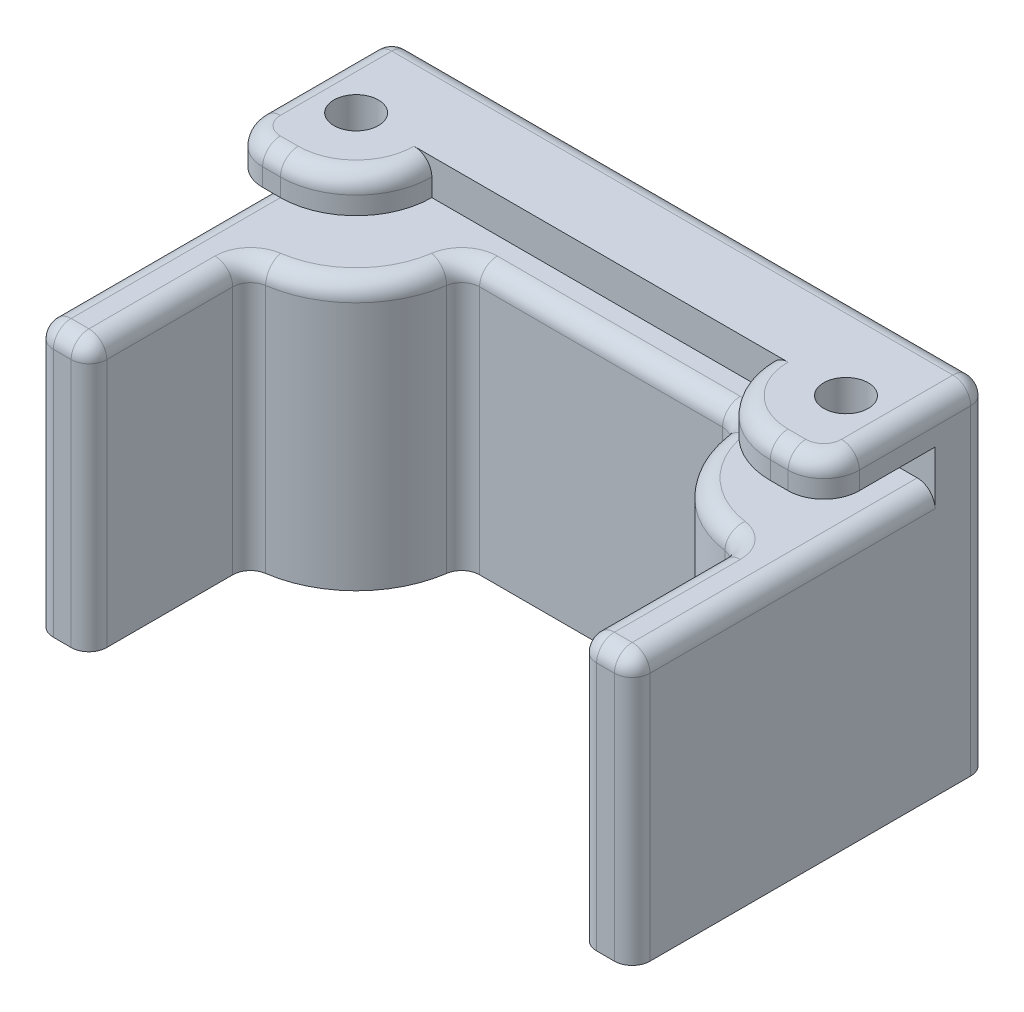
SolidWorks part; units mm, degrees
ref_plane "Front Plane" through (0, 0, 0) normal (0, 0, 1) x (1, 0, 0)
ref_plane "Top Plane" through (0, 0, 0) normal (0, 1, 0) x (1, 0, 0)
ref_plane "Right Plane" through (0, 0, 0) normal (1, 0, 0) x (0, 0, -1)
sketch "Sketch2" plane through (0, 0, 0) normal (0, 1, 0) x (1, 0, 0)
  line L0 (-16.75, -14) -> (-16.75, 4)
  line L1 (-15.75, 5) -> (15.75, 5)
  line L2 (-6.8218, 0) -> (6.8218, 0)
  line L3 (13.75, -6.9282) -> (13.75, -14)
  line L4 (14.75, -15) -> (15.75, -15)
  line L5 (-13.75, -6.9282) -> (-13.75, -14)
  line L6 (-14.75, -15) -> (-15.75, -15)
  line L7 (16.75, -14) -> (16.75, 4)
  arc A0 (-12.8929, -5.9385) -> (-7.8115, -0.8571) centre (-13.75, 0) ccw
  arc A1 (7.8115, -0.8571) -> (12.8929, -5.9385) centre (13.75, 0) ccw
  arc A2 (-13.75, -14) -> (-14.75, -15) centre (-14.75, -14) cw
  arc A3 (13.75, -14) -> (14.75, -15) centre (14.75, -14) ccw
  arc A4 (6.8218, 0) -> (7.8115, -0.8571) centre (6.8218, -1) cw
  arc A5 (13.75, -6.9282) -> (12.8929, -5.9385) centre (12.75, -6.9282) ccw
  arc A6 (-13.75, -6.9282) -> (-12.8929, -5.9385) centre (-12.75, -6.9282) cw
  arc A7 (-6.8218, 0) -> (-7.8115, -0.8571) centre (-6.8218, -1) ccw
  arc A8 (15.75, -15) -> (16.75, -14) centre (15.75, -14) ccw
  arc A9 (15.75, 5) -> (16.75, 4) centre (15.75, 4) cw
  arc A10 (-15.75, 5) -> (-16.75, 4) centre (-15.75, 4) ccw
  arc A11 (-15.75, -15) -> (-16.75, -14) centre (-15.75, -14) cw
  point P32 (0, 0)
  point P34 (0, 0)
  point P35 (0, 0)
  point P36 (0, 0)
  point P37 (0, 0)
  point P38 (0, 0)
  point P39 (0, 0)
  dimension "D1" = 6
  dimension "D3" = 1
  dimension "D4" = 1
  dimension "D5" = 15
  dimension "D8" = 27.5
  dimension "D2" = 27.5
  dimension "D6" = 3
  dimension "D7" = 5
  dimension "D9" = 13.75
extrude "Main body" add sketch "Sketch2" along normal blind 15
sketch "Sketch3" plane through (0, 15, 0) normal (0, 1, 0) x (1, 0, 0)
  line L0 (16.75, -14) -> (16.75, 4) construction
  line L1 (-16.75, 4) -> (-16.75, -14) construction
  line L2 (15.75, 5) -> (-15.75, 5) construction
  line L3 (16.75, 2) -> (16.75, 4)
  line L4 (-16.75, 4) -> (-16.75, 2)
  line L5 (15.75, 5) -> (-15.75, 5)
  line L6 (-16.75, 2) -> (16.75, 2)
  line L7 (-6.8218, 0) -> (6.8218, 0) construction
  arc A0 (16.75, 4) -> (15.75, 5) centre (15.75, 4) ccw construction
  arc A1 (-15.75, 5) -> (-16.75, 4) centre (-15.75, 4) ccw construction
  arc A2 (16.75, 4) -> (15.75, 5) centre (15.75, 4) ccw
  arc A3 (-15.75, 5) -> (-16.75, 4) centre (-15.75, 4) ccw
  dimension "D1" = 2
extrude "Extension for top flange" add sketch "Sketch3" along normal blind 2
sketch "Sketch4" plane through (0, 17, 0) normal (0, 1, 0) x (1, 0, 0)
  line L0 (16.75, -14) -> (16.75, 2) construction
  line L1 (16.75, 2) -> (16.75, 4) construction
  line L2 (15.75, 5) -> (-15.75, 5) construction
  line L3 (-16.75, 4) -> (-16.75, 2) construction
  line L4 (-16.75, 2) -> (-16.75, -14) construction
  line L5 (16.75, -2.25) -> (16.75, 2)
  line L6 (16.75, 2) -> (16.75, 4)
  line L7 (15.75, 5) -> (-15.75, 5)
  line L8 (-16.75, 4) -> (-16.75, 2)
  line L9 (-16.75, 2) -> (-16.75, -2.25)
  line L10 (-9.5, 0) -> (9.5, 0)
  line L11 (13.75, -4.25) -> (14.75, -4.25)
  line L12 (-13.75, -4.25) -> (-14.75, -4.25)
  arc A0 (16.75, 4) -> (15.75, 5) centre (15.75, 4) ccw construction
  arc A1 (-15.75, 5) -> (-16.75, 4) centre (-15.75, 4) ccw construction
  arc A2 (16.75, 4) -> (15.75, 5) centre (15.75, 4) ccw
  arc A3 (-15.75, 5) -> (-16.75, 4) centre (-15.75, 4) ccw
  circle A4 centre (-13.75, 0) radius 1.25
  circle A5 centre (13.75, 0) radius 1.25
  arc A6 (-12.8929, -5.9385) -> (-7.8115, -0.8571) centre (-13.75, 0) ccw construction
  arc A7 (7.8115, -0.8571) -> (12.8929, -5.9385) centre (13.75, 0) ccw construction
  arc A8 (9.5, 0) -> (13.75, -4.25) centre (13.75, 0) ccw
  arc A9 (-13.75, -4.25) -> (-9.5, 0) centre (-13.75, 0) ccw
  circle A10 centre (13.75, 0) radius 4.25 construction
  circle A11 centre (-13.75, 0) radius 4.25 construction
  arc A12 (14.75, -4.25) -> (16.75, -2.25) centre (14.75, -2.25) ccw
  arc A13 (-14.75, -4.25) -> (-16.75, -2.25) centre (-14.75, -2.25) cw
  dimension "D1" = 2.5
  dimension "D3" = 2
  dimension "D2" = 3
extrude "Top camera flange" add sketch "Sketch4" along normal blind 2
sketch "Sketch5" plane through (0, 15, 0) normal (0, 1, 0) x (1, 0, 0)
  circle A0 centre (-13.75, 0) radius 1
  circle A1 centre (13.75, 0) radius 1
  dimension "D1" = 2
extrude "M2 screwhole" cut sketch "Sketch5" against normal through all both and the other way through all
fillet "Fillet1" radius 1 28 edges at (10.7448, 19, 3.0052) (14.25, 19, 4.25) (16.1642, 19, 3.6642) (16.75, 19, -0.875) (16.4571, 19, -4.7071) (-10.7448, 19, 3.0052) (-14.25, 19, 4.25) (-16.1642, 19, 3.6642) (-16.75, 19, -0.875) (-16.4571, 19, -4.7071) (0, 19, -5) (-16.75, 15, 6) (-16.4571, 15, 14.7071) (-15.25, 15, 15) (-14.0429, 15, 14.7071) (-13.75, 15, 10.4641) (-13.5059, 15, 6.2735) (-9.5074, 15, 4.2426) (-7.4765, 15, 0.2441) (16.75, 15, 6) (16.4571, 15, 14.7071) (15.25, 15, 15) (14.0429, 15, 14.7071) (13.75, 15, 10.4641) (13.5059, 15, 6.2735) (9.5074, 15, 4.2426) (7.4765, 15, 0.2441) (0, 15, 0)
